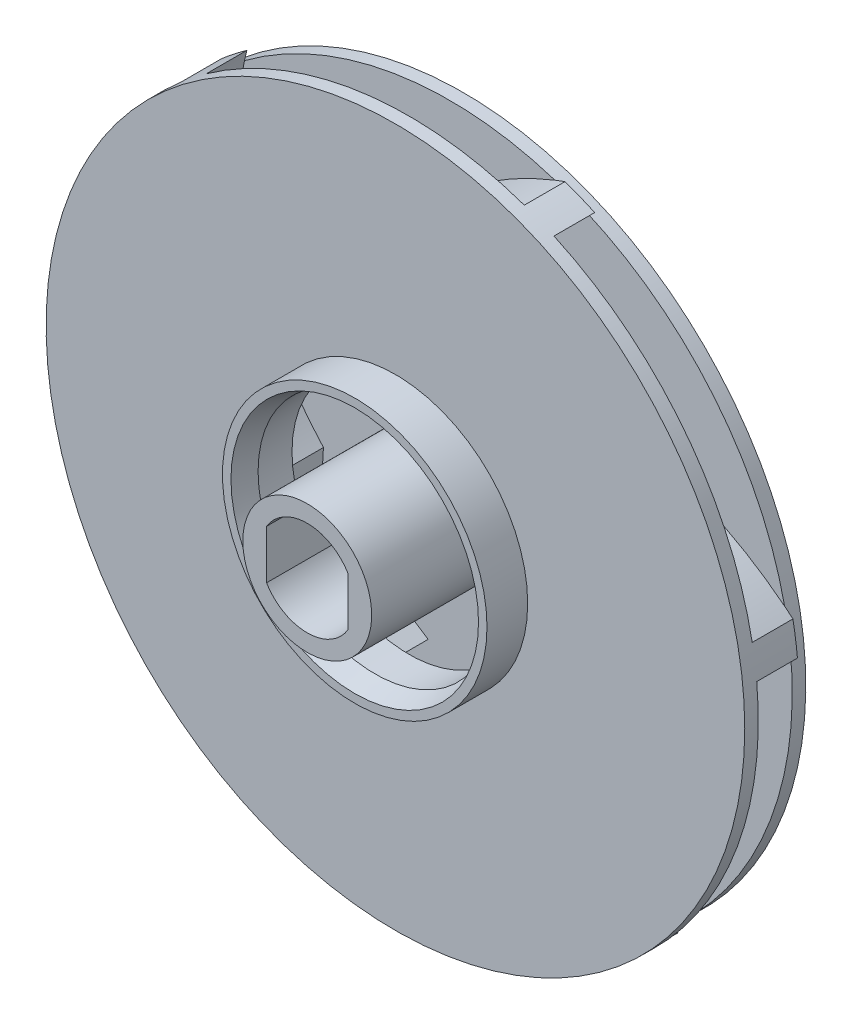
SolidWorks part; units mm, degrees
ref_plane "Ön Düzlem" through (0, 0, 0) normal (0, 0, 1) x (1, 0, 0)
ref_plane "Üst Düzlem" through (0, 0, 0) normal (0, 1, 0) x (1, 0, 0)
ref_plane "Sağ Düzlem" through (0, 0, 0) normal (1, 0, 0) x (0, 0, -1)
sketch "Sketch1" plane through (0, 0, 0) normal (0, 0, 1) x (1, 0, 0)
  circle A0 centre (0, 0) radius 51.5
extrude "Boss-Extrude1" add sketch "Sketch1" along normal blind 2
sketch "Sketch2" plane through (0, 0, 2) normal (0, 0, 1) x (1, 0, 0)
  circle A0 centre (0, 0) radius 17.25
extrude "Cut-Extrude1" cut sketch "Sketch2" against normal blind 2
sketch "Sketch4" plane through (0, 0, 0) normal (0, 0, -1) x (-1, 0, 0)
  line L0 (-17.25, 0) -> (-51.5, 0) construction
  line L1 (15.6595, 12.7157) -> (12.021, 14.5535)
  circle A0 centre (0, 0) radius 17.25 construction
  circle A1 centre (0, 0) radius 51.5 construction
  arc A2 (15.6595, 12.7157) -> (-17, 48.6133) centre (-34.375, 0) ccw
  arc A3 (12.021, 14.5535) -> (-21.3745, 46.8549) centre (-34.375, 0) ccw
  arc A4 (-17, 48.6133) -> (-21.3745, 46.8549) centre (0, 0) ccw
  circle A6 centre (-34.375, 0) radius 51.625 construction
  circle A7 centre (-34.375, 0) radius 48.625 construction
  dimension "D1" = 3
extrude "Boss-Extrude3" add sketch "Sketch4" along normal blind 6
pattern_circular "CirPattern2" count 6 over 360 about axis through (0, 0, 0) along (0, 0, 1) of "Boss-Extrude3"
sketch "Sketch5" plane through (0, 0, 2) normal (0, 0, 1) x (1, 0, 0)
  circle A0 centre (0, 0) radius 17.25 construction
  circle A1 centre (0, 0) radius 17.25
  circle A2 centre (0, 0) radius 19.5
extrude "Boss-Extrude4" add sketch "Sketch5" along normal blind 6
chamfer "Chamfer1" distance 1 distance2 3 1 edges at (17.25, 0, 8)
sketch "Sketch6" plane through (0, 0, -6) normal (0, 0, -1) x (-1, 0, 0)
  circle A0 centre (0, 0) radius 51.5
extrude "Boss-Extrude5" add sketch "Sketch6" along normal blind 2
sketch "Sketch7" plane through (0, 0, -8) normal (0, 0, -1) x (-1, 0, 0)
  circle A0 centre (0, 0) radius 19.5
extrude "Boss-Extrude6" add sketch "Sketch7" along normal blind 5
sketch "Sketch8" plane through (0, 0, -13) normal (0, 0, -1) x (-1, 0, 0)
  circle A0 centre (0, 0) radius 9.5
extrude "Boss-Extrude7" add sketch "Sketch8" against normal blind 28
sketch "Sketch9" plane through (0, 0, 15) normal (0, 0, 1) x (1, 0, 0)
  line L0 (-7, 0) -> (0, 0) construction
  line L1 (7, 0) -> (0, 0) construction
  line L2 (0, 0) -> (0, 7) construction
  line L3 (0, 7) -> (0, -7) construction
  line L4 (6, 0) -> (6, 3.6056)
  line L5 (-6, 0) -> (-6, 3.6056)
  line L6 (6, 0) -> (6, -3.6056)
  line L7 (-6, 0) -> (-6, -3.6056)
  line L8 (6, 0) -> (7, 0) construction
  line L9 (-6, 0) -> (-6, 7) construction
  line L10 (6, 0) -> (6, 7) construction
  arc A0 (-6, -3.6056) -> (6, -3.6056) centre (0, 0) ccw
  arc A1 (6, 3.6056) -> (-6, 3.6056) centre (0, 0) ccw
  dimension "D1" = 6
  dimension "D2" = 6
extrude "Cut-Extrude2" cut sketch "Sketch9" against normal through all
sketch "Sketch10" plane through (0, 0, -13) normal (0, 0, -1) x (-1, 0, 0)
  circle A0 centre (0, 0) radius 7.5
extrude "Cut-Extrude3" cut sketch "Sketch10" against normal blind 2
sketch "Sketch11" plane through (0, 0, -13) normal (0, 0, -1) x (-1, 0, 0)
  circle A0 centre (0, 0) radius 12.5
  circle A1 centre (0, 0) radius 15.5
extrude "Cut-Extrude4" cut sketch "Sketch11" against normal blind 3
sketch "Sketch12" plane through (0, 0, -6) normal (0, 0, 1) x (1, 0, 0)
  circle A0 centre (0, 0) radius 50.5
  circle A1 centre (0, 0) radius 57.8267
extrude "Cut-Extrude5" cut sketch "Sketch12" against normal blind 50
